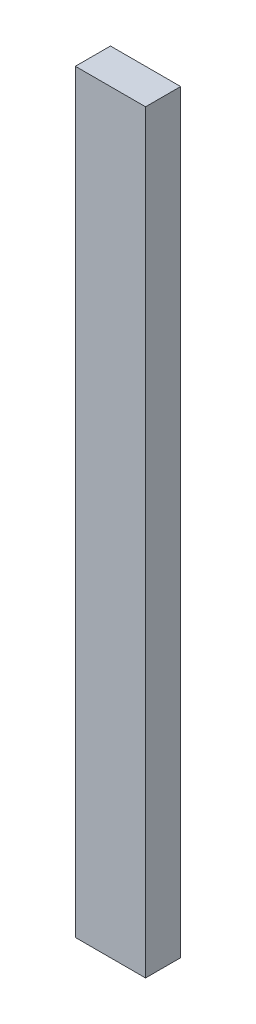
SolidWorks part; units mm, degrees
ref_plane "Front Plane" through (0, 0, 0) normal (0, 0, 1) x (1, 0, 0)
ref_plane "Top Plane" through (0, 0, 0) normal (0, 1, 0) x (1, 0, 0)
ref_plane "Right Plane" through (0, 0, 0) normal (1, 0, 0) x (0, 0, -1)
sketch "Sketch1" plane through (0, 0, 0) normal (0, 0, 1) x (1, 0, 0)
  line L1 (12.7, -7.9375) -> (0, -7.9375)
  line L2 (12.7, -7.9375) -> (12.7, -144.4625)
  line L3 (12.7, -144.4625) -> (0, -144.4625)
  line L4 (0, -7.9375) -> (0, -144.4625)
extrude "Boss-Extrude1" add sketch "Sketch1" along normal blind 6.35
